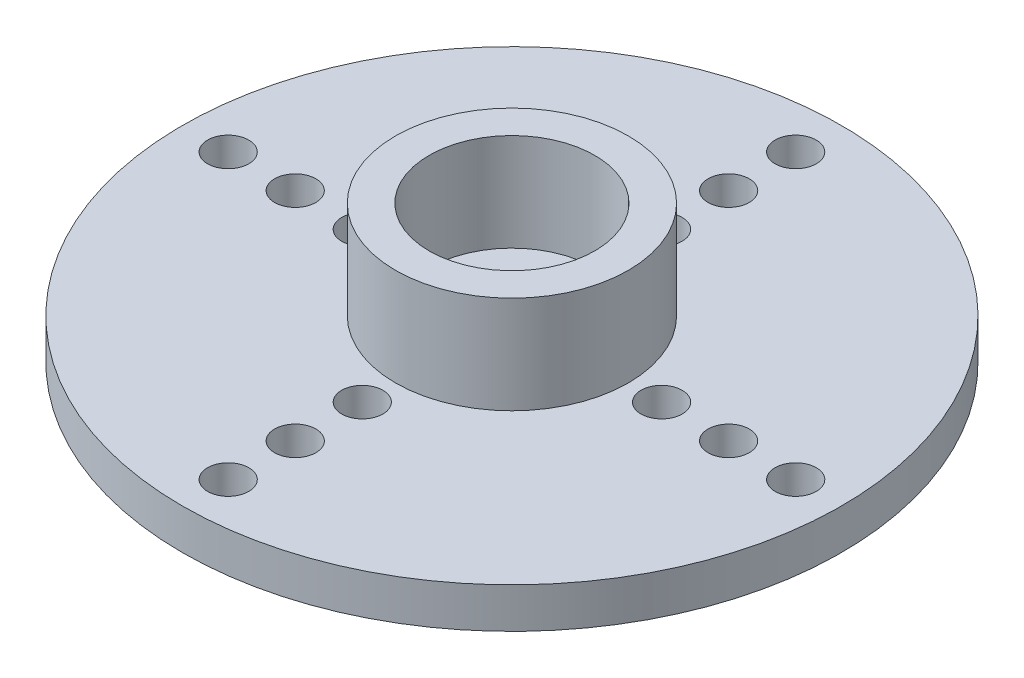
SolidWorks part; units mm, degrees
ref_plane "Front Plane" through (0, 0, 0) normal (0, 0, 1) x (1, 0, 0)
ref_plane "Top Plane" through (0, 0, 0) normal (0, 1, 0) x (1, 0, 0)
ref_plane "Right Plane" through (0, 0, 0) normal (1, 0, 0) x (0, 0, -1)
sketch "Sketch1" plane through (0, 0, 0) normal (0, 1, 0) x (1, 0, 0)
  circle A0 centre (0, 0) radius 9.9568
  dimension "D1" = 19.9136
extrude "Boss-Extrude1" add sketch "Sketch1" along normal blind 1.2192
sketch "Sketch2" plane through (0, 1.2192, 0) normal (0, 1, 0) x (1, 0, 0)
  circle A0 centre (0, 0) radius 3.5179
  circle A1 centre (0, 0) radius 2.5019
  dimension "D1" = 7.0358
  dimension "D2" = 5.0038
extrude "Boss-Extrude2" add sketch "Sketch2" along normal blind 2.9464
sketch "Sketch3" plane through (0, 1.2192, 0) normal (0, 1, 0) x (1, 0, 0)
  line L0 (0, 1.6867) -> (0, -1.6985) construction
  line L1 (-1.5502, 0) -> (1.8377, 0) construction
  line L2 (0, 0) -> (-4.5212, 0) construction
  line L3 (-8.5725, 0) -> (-6.5469, 0) construction
  line L4 (0, 0) -> (0, 4.5212) construction
  circle A0 centre (0, 0) radius 1.0795
  circle A1 centre (-4.5212, 0) radius 0.6223
  circle A2 centre (-6.5469, 0) radius 0.6223
  circle A3 centre (-8.5725, 0) radius 0.6223
  circle A4 centre (8.5725, 0) radius 0.6223
  circle A5 centre (6.5469, 0) radius 0.6223
  circle A6 centre (4.5212, 0) radius 0.6223
  circle A7 centre (0, 4.5212) radius 0.6223
  circle A8 centre (0, 6.5469) radius 0.6223
  circle A9 centre (0, 8.5725) radius 0.6223
  circle A10 centre (0, -4.5212) radius 0.6223
  circle A11 centre (0, -6.5469) radius 0.6223
  circle A12 centre (0, -8.5725) radius 0.6223
  dimension "D1" = 2.159
  dimension "D3" = 1.2446
  dimension "D4" = 9.0424
  dimension "D5" = 17.145
  dimension "D7" = 90
  dimension "D2" = 3
  dimension "D6" = 2
extrude "Cut-Extrude1" cut sketch "Sketch3" against normal through all
